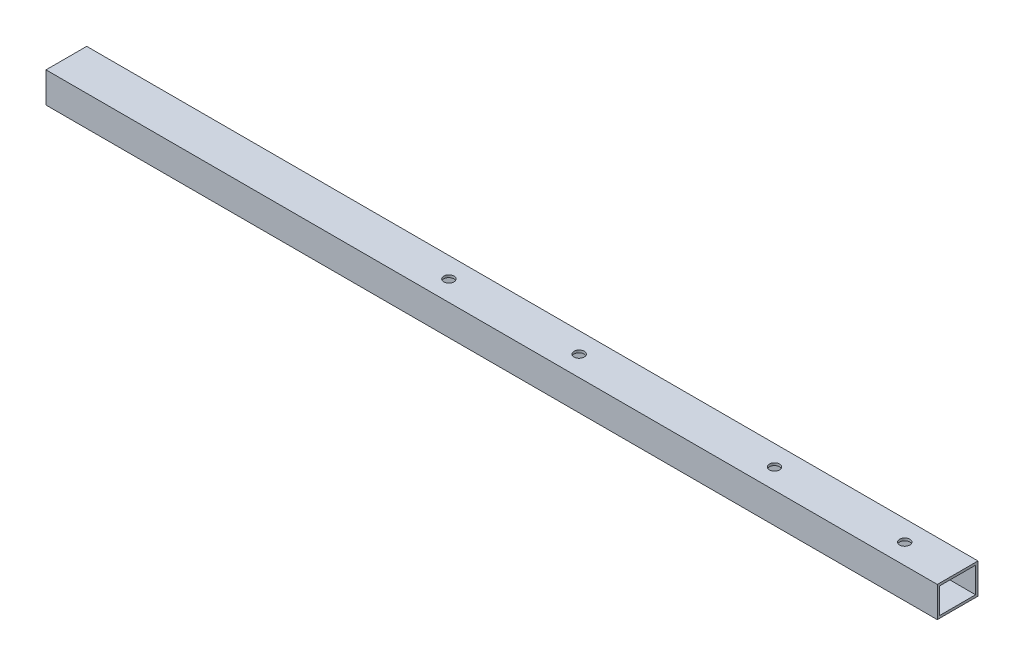
SolidWorks part; units mm, degrees
material "6061 合金"
ref_plane "前视基准面" through (0, 0, 0) normal (0, 0, 1) x (1, 0, 0)
ref_plane "上视基准面" through (0, 0, 0) normal (0, 1, 0) x (1, 0, 0)
ref_plane "右视基准面" through (0, 0, 0) normal (1, 0, 0) x (0, 0, -1)
sketch3d "3D草图1"
  line L0 (0, 0, 0) -> (438, 0, 0)
  dimension "D1" = 438
other "方形管 15 X 20 X 1.2(1)"
ref_plane "基准面1" through (0, 0, 0) normal (1, 0, 0) x (0, 0, -1)
sketch "Sketch1" plane through (0, 0, 0) normal (1, 0, 0) x (0, 0, -1)
  line L0 (-8.8, 6.3) -> (8.8, 6.3)
  line L1 (-10, 7.5) -> (10, 7.5)
  line L2 (-10, 7.5) -> (-10, -7.5)
  line L3 (-10, -7.5) -> (10, -7.5)
  line L4 (10, 7.5) -> (10, -7.5)
  line L5 (-10, 7.5) -> (10, -7.5) construction
  line L6 (-10, -7.5) -> (10, 7.5) construction
  line L7 (8.8, 6.3) -> (8.8, -6.3)
  line L8 (-8.8, -6.3) -> (8.8, -6.3)
  line L9 (-8.8, 6.3) -> (-8.8, -6.3)
  point P0 (0, 0)
  point P9 (0, 0)
  dimension "D1" = 15
  dimension "D2" = 20
  dimension "D3" = 1.2
sketch "草图3" plane through (0, 7.5, 0) normal (0, 1, 0) x (1, 0, 0)
  line L0 (80.6059, 0) -> (438, 0) construction
  line L1 (438, 10) -> (438, -10) construction
  line L3 (0, 10) -> (0, -10) construction
  circle A0 centre (188, 0) radius 2.5
  circle A1 centre (252, 0) radius 2.5
  circle A2 centre (348, 0) radius 2.5
  circle A3 centre (412, 0) radius 2.5
  point P10 (0, 0)
  point P13 (438, 0)
  dimension "D5" = 5
  dimension "D1" = 188
  dimension "D2" = 64
  dimension "D3" = 160
  dimension "D4" = 64
extrude "切除-拉伸1" cut sketch "草图3" against normal through all
